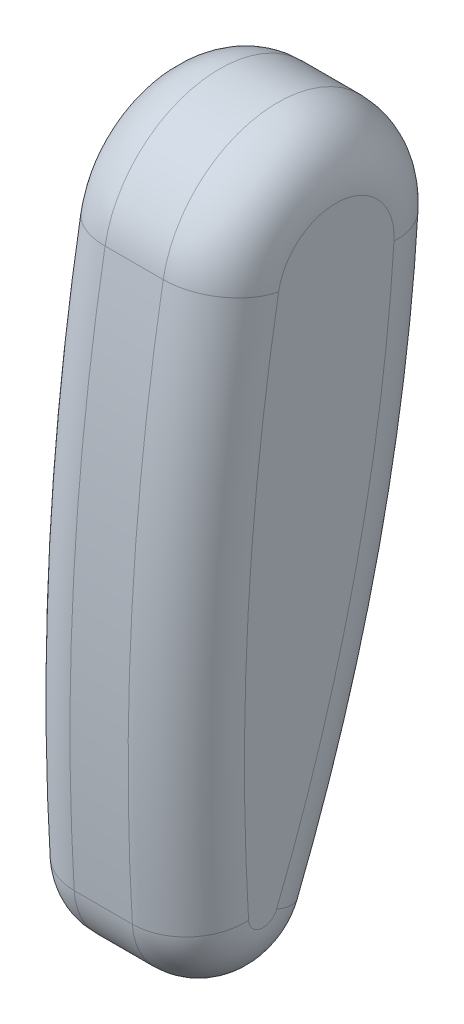
SolidWorks part; units mm, degrees
material "PW90:Mi:0:29:C1:0:1:2:Re:16:"
ref_plane "XY" through (0, 0, 0) normal (0, 0, 1) x (1, 0, 0)
ref_plane "YZ" through (0, 0, 0) normal (0, 1, 0) x (1, 0, 0)
ref_plane "XZ" through (0, 0, 0) normal (1, 0, 0) x (0, 0, -1)
ref_plane "Leg-plane" through (114.3, 0, 0) normal (1, 0, 0) x (0, 0, -1)
sketch "Sketch6" plane through (114.3, 0, 0) normal (1, 0, 0) x (0, 0, -1)
  line L0 (-24.1632, -755.7123) -> (39.4667, -302.9618) construction
  line L1 (0, 432.2232) -> (0, -432.2232) construction
  arc A0 (140.8633, -309.3875) -> (-60.6009, -285.3826) centre (39.4667, -302.9618) ccw
  arc A1 (-87.5476, -759.5429) -> (34.7899, -779.3084) centre (-24.1632, -755.7123) ccw
  arc A2 (-87.5476, -759.5429) -> (-60.6009, -285.3826) centre (1940.7519, -636.9659) cw
  arc A3 (140.8633, -309.3875) -> (34.7899, -779.3084) centre (-1380.0857, -213.0019) cw
  dimension "D3" = 101.6
  dimension "D4" = 1524
  dimension "D5" = 2032
  dimension "D6" = 63.5
  dimension "D1" = 457.2
  dimension "D2" = 8
extrude "Base-Extrude" add sketch "Sketch6" along normal mid plane 152.4
fillet "Fillet1" radius 50.8
